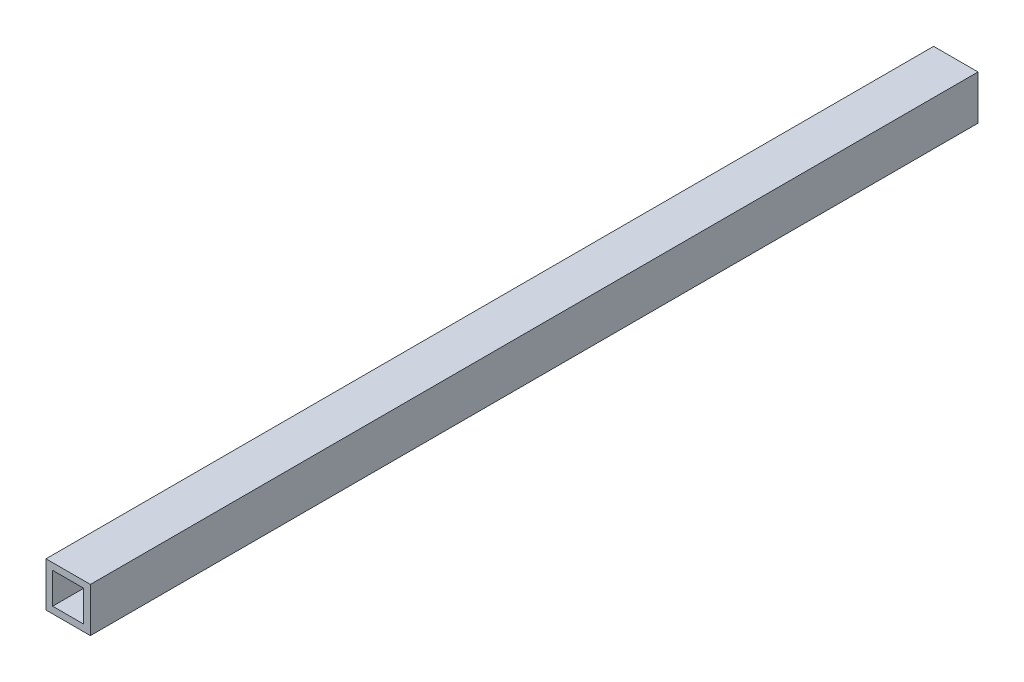
SolidWorks part; units mm, degrees
ref_plane "前视基准面" through (0, 0, 0) normal (0, 0, 1) x (1, 0, 0)
ref_plane "上视基准面" through (0, 0, 0) normal (0, 1, 0) x (1, 0, 0)
ref_plane "右视基准面" through (0, 0, 0) normal (1, 0, 0) x (0, 0, -1)
other "Configuration Table"
sketch "草图1" plane through (0, 0, 0) normal (0, 0, 1) x (1, 0, 0)
  line L1 (-5, 5) -> (5, 5)
  line L2 (-5, 5) -> (-5, -5)
  line L3 (-5, -5) -> (5, -5)
  line L4 (5, 5) -> (5, -5)
  line L5 (-5, 5) -> (5, -5) construction
  line L6 (-5, -5) -> (5, 5) construction
  line L7 (-3.5, 3.5) -> (3.5, 3.5)
  line L8 (-3.5, 3.5) -> (-3.5, -3.5)
  line L9 (-3.5, -3.5) -> (3.5, -3.5)
  line L10 (3.5, 3.5) -> (3.5, -3.5)
  line L11 (-3.5, 3.5) -> (3.5, -3.5) construction
  line L12 (-3.5, -3.5) -> (3.5, 3.5) construction
  point P0 (0, 0)
  point P5 (0, 0)
  dimension "D1" = 10
  dimension "D2" = 1.5
  dimension "D3" = 10
extrude "凸台-拉伸1" add sketch "草图1" along normal blind 200
